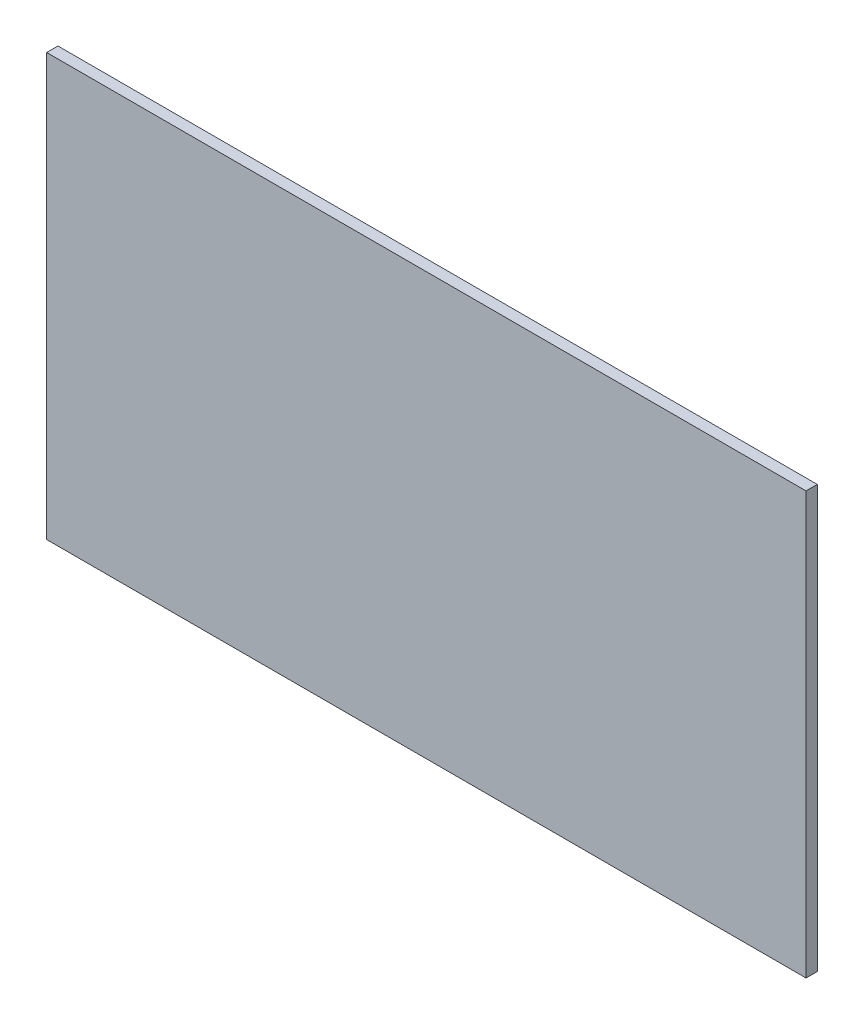
SolidWorks part; units mm, degrees
ref_plane "Front Plane" through (0, 0, 0) normal (0, 0, 1) x (1, 0, 0)
ref_plane "Top Plane" through (0, 0, 0) normal (0, 1, 0) x (1, 0, 0)
ref_plane "Right Plane" through (0, 0, 0) normal (1, 0, 0) x (0, 0, -1)
sketch "Sketch1" plane through (0, 0, 0) normal (0, 0, 1) x (1, 0, 0)
  line L1 (-67.5, -37.5) -> (67.5, -37.5)
  line L2 (-67.5, -37.5) -> (-67.5, 37.5)
  line L3 (-67.5, 37.5) -> (67.5, 37.5)
  line L4 (67.5, -37.5) -> (67.5, 37.5)
  line L5 (-67.5, -37.5) -> (67.5, 37.5) construction
  line L6 (-67.5, 37.5) -> (67.5, -37.5) construction
  point P0 (0, 0)
  dimension "D1" = 135
  dimension "D2" = 75
extrude "Boss-Extrude1" add sketch "Sketch1" along normal blind 2
